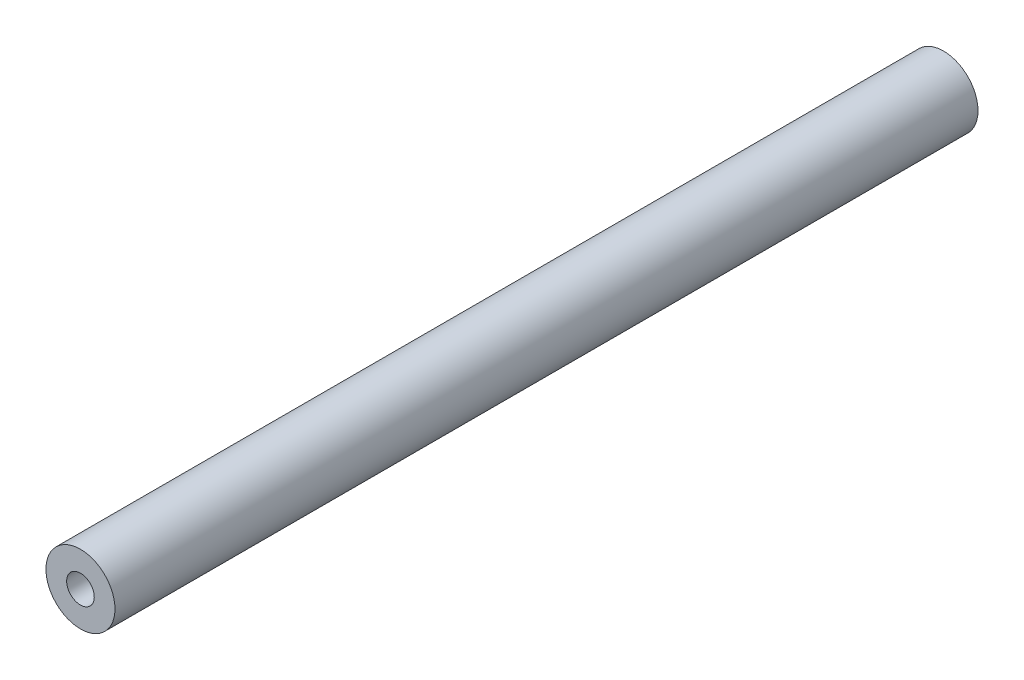
SolidWorks part; units mm, degrees
ref_plane "前视基准面" through (0, 0, 0) normal (0, 0, 1) x (1, 0, 0)
ref_plane "上视基准面" through (0, 0, 0) normal (0, 1, 0) x (1, 0, 0)
ref_plane "右视基准面" through (0, 0, 0) normal (1, 0, 0) x (0, 0, -1)
other "Configuration Table"
sketch "草图1" plane through (0, 0, 0) normal (0, 0, 1) x (1, 0, 0)
  circle A0 centre (0, 0) radius 4
  circle A1 centre (0, 0) radius 1.6
extrude "100mm铝柱" add sketch "草图1" along normal blind 100
